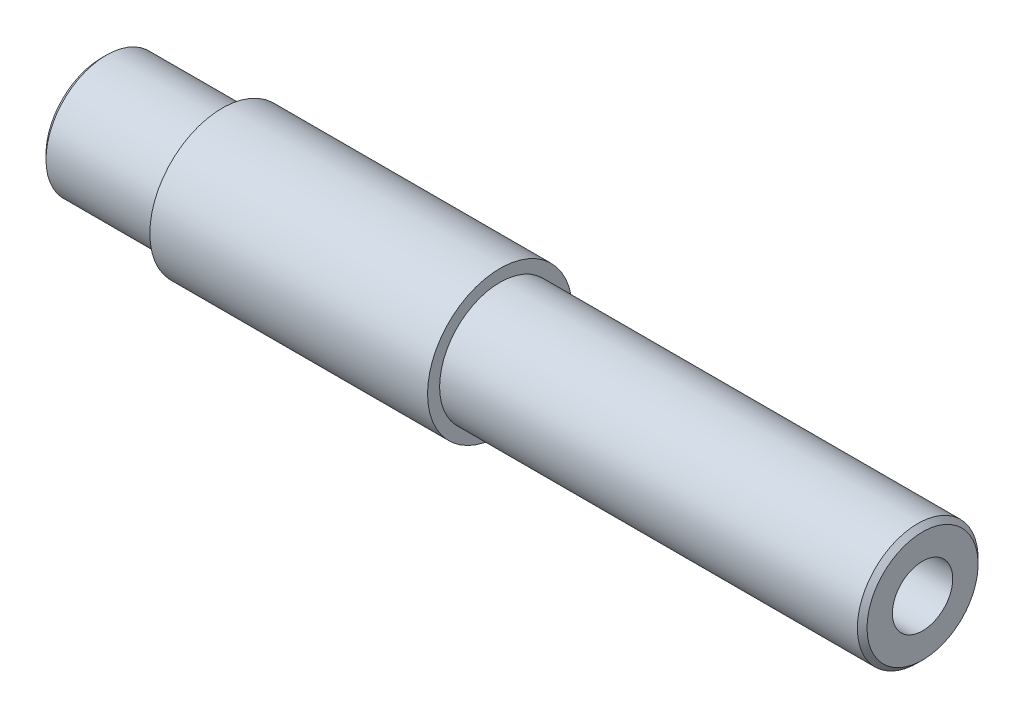
SolidWorks part; units mm, degrees
material "Acier allié"
ref_plane "Face" through (0, 0, 0) normal (0, 0, 1) x (1, 0, 0)
ref_plane "Dessus" through (0, 0, 0) normal (0, 1, 0) x (1, 0, 0)
ref_plane "Droite" through (0, 0, 0) normal (1, 0, 0) x (0, 0, -1)
sketch "Esquisse2" plane through (0, 0, 0) normal (0, 0, 1) x (1, 0, 0)
  line L0 (-17, 0) -> (17, 0) construction
  line L1 (17, 0) -> (17, 2.5)
  line L2 (17, 2.5) -> (-0.5, 2.5)
  line L3 (-0.5, 2.5) -> (-0.5, 3)
  line L6 (-0.5, 3) -> (-17, 3)
  line L7 (-17, 3) -> (-17, 0)
  line L8 (-17, 0) -> (17, 0)
  dimension "D1" = 17.5
  dimension "D2" = 5
  dimension "D4" = 16.5
  dimension "D5" = 6
revolve "Révolution1" add sketch "Esquisse2" angle 360 about L0
hole_wizard "Trou taraudé M31" positions "Esquisse5" profile "Esquisse4" tap size "M3" standard "Iso"
sketch "Esquisse5" plane through (17, 0, 0) normal (1, 0, 0) x (0, 0, -1)
  point P0 (0, 0)
sketch "Esquisse4" plane through (17, 0, 0) normal (0, 1, 0) x (0, 0, -1)
  line L0 (0, 0) -> (0, 8.7511)
  line L1 (0, 8.7511) -> (1.25, 8)
  line L2 (1.25, 8) -> (1.25, 0)
  line L5 (1.25, 0) -> (0, 0)
  line L10 (0, 8.7511) -> (-1.25, 8) construction
  line L11 (0, -6.35) -> (0, 107.95) construction
  dimension "Diamètre du trou pour taraudage" = 2.5
  dimension "Profondeur du trou pour taraudage" = 8
  dimension "Angle de pointe" = 118
cosmetic thread "Filetage de perçage1" parameters "D1"=6, "D2"=3
sketch "Esquisse7" plane through (0, 0, 0) normal (0, 0, 1) x (1, 0, 0)
  line L0 (-17, 0) -> (-0.5, 0) construction
  line L1 (-17, 3) -> (-12, 3)
  line L2 (-17, 3) -> (-17, 2.5)
  line L3 (-17, 2.5) -> (-12, 2.5)
  line L4 (-12, 3) -> (-12, 2.5)
  line L5 (-17, 3) -> (-17, -3) construction
  line L6 (-0.5, -2.5) -> (-0.5, 2.5) construction
  dimension "D1" = 5
  dimension "D2" = 5
revolve "Enlèvement de matière-Révolution1" cut sketch "Esquisse7" angle 360 about L0
chamfer "Chanfrein1" distance 0.2 angle 45 2 edges at (-17, 0, 2.5) (17, 0, 2.5)
hole_wizard "Trou taraudé M32" positions "Esquisse9" profile "Esquisse8" tap size "M3" standard "Iso"
sketch "Esquisse9" plane through (-17, 0, 0) normal (-1, 0, 0) x (0, 0, 1)
  point P0 (0, 0)
sketch "Esquisse8" plane through (-17, 0, 0) normal (0, 1, 0) x (0, 0, 1)
  line L0 (0, 0) -> (0, 8.7511)
  line L1 (0, 8.7511) -> (1.25, 8)
  line L2 (1.25, 8) -> (1.25, 0)
  line L5 (1.25, 0) -> (0, 0)
  line L10 (0, 8.7511) -> (-1.25, 8) construction
  line L11 (0, -6.35) -> (0, 107.95) construction
  dimension "Diamètre du trou pour taraudage" = 2.5
  dimension "Profondeur du trou pour taraudage" = 8
  dimension "Angle de pointe" = 118
cosmetic thread "Filetage de perçage2" parameters "D1"=6, "D2"=3
